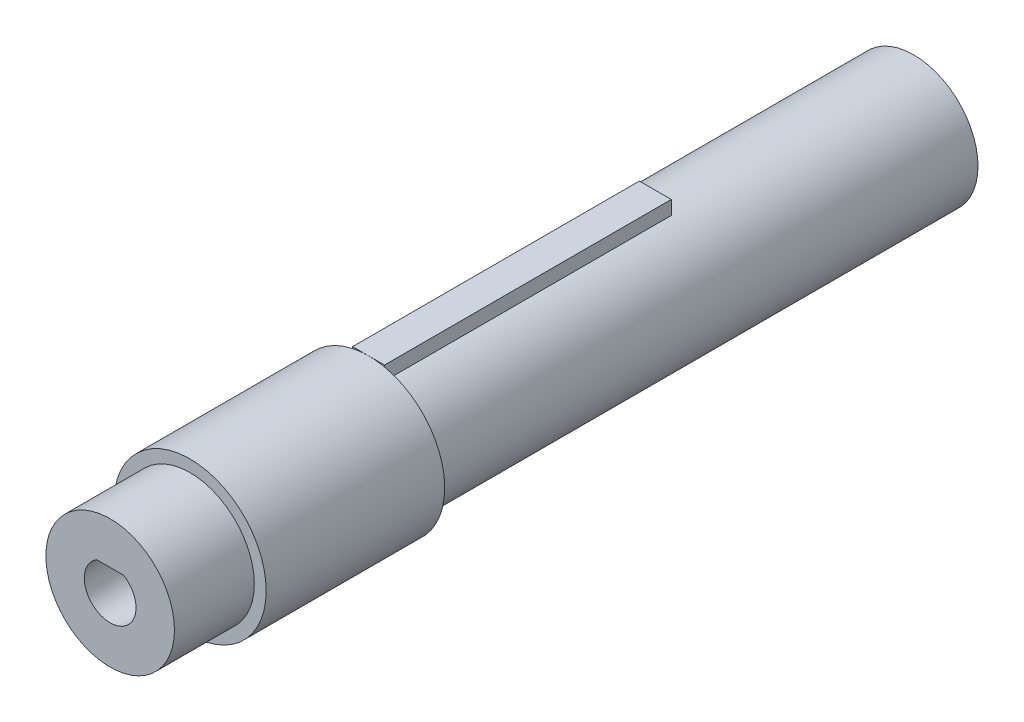
SolidWorks part; units mm, degrees
ref_plane "Front Plane" through (0, 0, 0) normal (0, 0, 1) x (1, 0, 0)
ref_plane "Top Plane" through (0, 0, 0) normal (0, 1, 0) x (1, 0, 0)
ref_plane "Right Plane" through (0, 0, 0) normal (1, 0, 0) x (0, 0, -1)
sketch "Sketch1" plane through (0, 0, 0) normal (0, 0, 1) x (1, 0, 0)
  line L0 (-1.3463, 2.195) -> (1.3463, 2.195)
  circle A0 centre (0, 0) radius 6.4
  arc A1 (-1.3463, 2.195) -> (1.3463, 2.195) centre (0, 0) ccw
  point P6 (0, 2.195)
  point P7 (0, -2.575)
  dimension "D1" = 4.77
  dimension "D2" = 2.575
  dimension "D3" = 12.8
extrude "Boss-Extrude1" add sketch "Sketch1" along normal blind 80
ref_plane "Plane6" through (0, 0, 40) normal (0, 0, 1) x (1, 0, 0)
sketch "Sketch9" plane through (0, 0, 40) normal (0, 0, 1) x (1, 0, 0)
  line L0 (-1.5875, 3.5819) -> (-1.5875, 7.5819)
  line L1 (-1.5875, 7.5819) -> (1.5875, 7.5819)
  line L2 (1.5875, 7.5819) -> (1.5875, 3.5819)
  line L3 (-1.5875, 3.5819) -> (1.5875, 3.5819)
  circle A0 centre (0, 0) radius 7.5819 construction
  circle A3 centre (0, 0) radius 6.4 construction
  point P0 (-1.5875, 3.5819)
  point P1 (1.5875, 3.5819)
  point P9 (0, 7.5819)
  point P11 (0, 6.4)
  dimension "D4" = 15.1638
  dimension "D1" = 3.175
  dimension "D2" = 4
extrude "Boss-Extrude2" add sketch "Sketch9" along normal blind 14.275 and the other way blind 14.275
sketch "Sketch10" plane through (0, 0, 80) normal (0, 0, 1) x (1, 0, 0)
  circle A0 centre (0, 0) radius 7.5819
  circle A1 centre (0, 0) radius 5
  dimension "D1" = 15.1638
  dimension "D2" = 10
extrude "Boss-Extrude3" add sketch "Sketch10" against normal up to surface (17.7748 mm away) from offset 7.9502 up to face at (0, 6.9409, 54.275)
